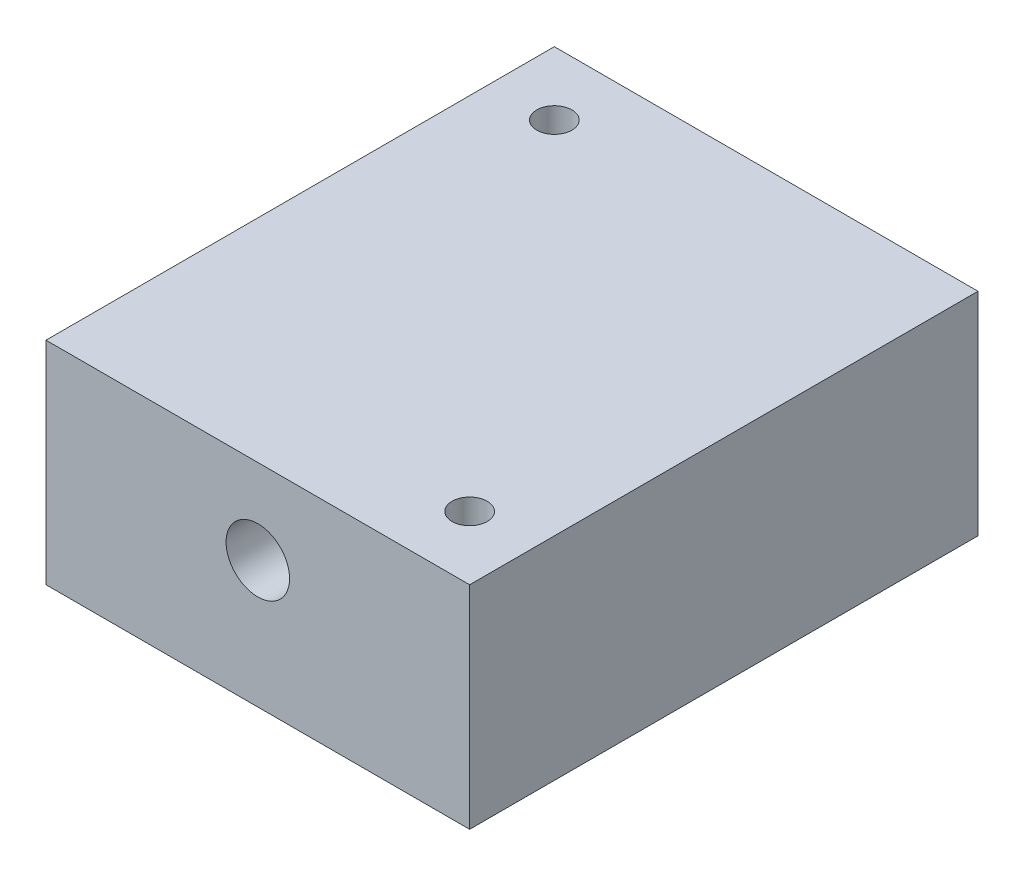
SolidWorks part; units mm, degrees
ref_plane "Ebene vorne" through (0, 0, 0) normal (0, 0, 1) x (1, 0, 0)
ref_plane "Ebene oben" through (0, 0, 0) normal (0, 1, 0) x (1, 0, 0)
ref_plane "Ebene rechts" through (0, 0, 0) normal (1, 0, 0) x (0, 0, -1)
sketch "Skizze1" plane through (0, 0, 0) normal (0, 0, 1) x (1, 0, 0)
  line L1 (50, -25) -> (-50, -25)
  line L2 (50, -25) -> (50, 25)
  line L3 (50, 25) -> (-50, 25)
  line L4 (-50, -25) -> (-50, 25)
  line L5 (50, -25) -> (-50, 25) construction
  line L6 (50, 25) -> (-50, -25) construction
  point P1 (0, 0)
  dimension "D1" = 50
  dimension "D2" = 100
extrude "Aufsatz-Linear austragen1" add sketch "Skizze1" along normal blind 120
sketch "Skizze2" plane through (0, 25, 0) normal (0, 1, 0) x (1, 0, 0)
  line L0 (50, -120) -> (-50, -120) construction
  line L1 (50, -120) -> (50, 0) construction
  line L2 (-50, -120) -> (-50, 0) construction
  line L3 (50, 0) -> (-50, 0) construction
  circle A0 centre (-35, -15) radius 15
  circle A1 centre (35, -105) radius 15
  dimension "D1" = 30
  dimension "D2" = 30
hole_wizard "Kernloch für M8 Helicoil1" positions "Skizze4" profile "Skizze5" hole size "M8x1.25" standard "ANSI Metrisch"
sketch "Skizze4" plane through (0, 25, 0) normal (0, 1, 0) x (1, 0, 0)
  point P0 (35, -105)
  point P5 (-35, -15)
sketch "Skizze5" plane through (35, 25, 105) normal (1, 0, 0) x (0, 0, 1)
  line L0 (0, 0) -> (0, 22.4936)
  line L1 (0, 22.4936) -> (4.15, 20)
  line L2 (4.15, 20) -> (4.15, 0)
  line L5 (4.15, 0) -> (0, 0)
  line L10 (0, 22.4936) -> (-4.15, 20) construction
  line L11 (0, -6.35) -> (0, 107.95) construction
  dimension "Bohrerdurchmesser" = 8.3
  dimension "Bohrungstiefe" = 20
  dimension "Spitzenwinkel" = 118
hole_wizard "Stirnsenkung für M8 Senkschraube (Kopf Button)1" positions "Skizze9" profile "Skizze8" counterbore size "M8" standard "ANSI Metrisch" end condition through all
sketch "Skizze9" plane through (0, 0, 120) normal (0, 0, 1) x (1, 0, 0)
  point P0 (0, 5)
sketch "Skizze8" plane through (0, 5, 120) normal (1, 0, 0) x (0, -1, 0)
  line L0 (0, 0) -> (0, 120)
  line L1 (0, 120) -> (4.5, 120)
  line L3 (4.5, 120) -> (4.5, 116)
  line L4 (4.5, 116) -> (7.5, 116)
  line L5 (7.5, 116) -> (7.5, 0)
  line L7 (7.5, 0) -> (0, 0)
  line L11 (0, -6.35) -> (0, 107.95) construction
  dimension "Bohrerdurchmesser" = 9
  dimension "Bohrungstiefe" = 120
  dimension "Senkdurchmesser2" = 15
  dimension "Senktiefe2" = 116
